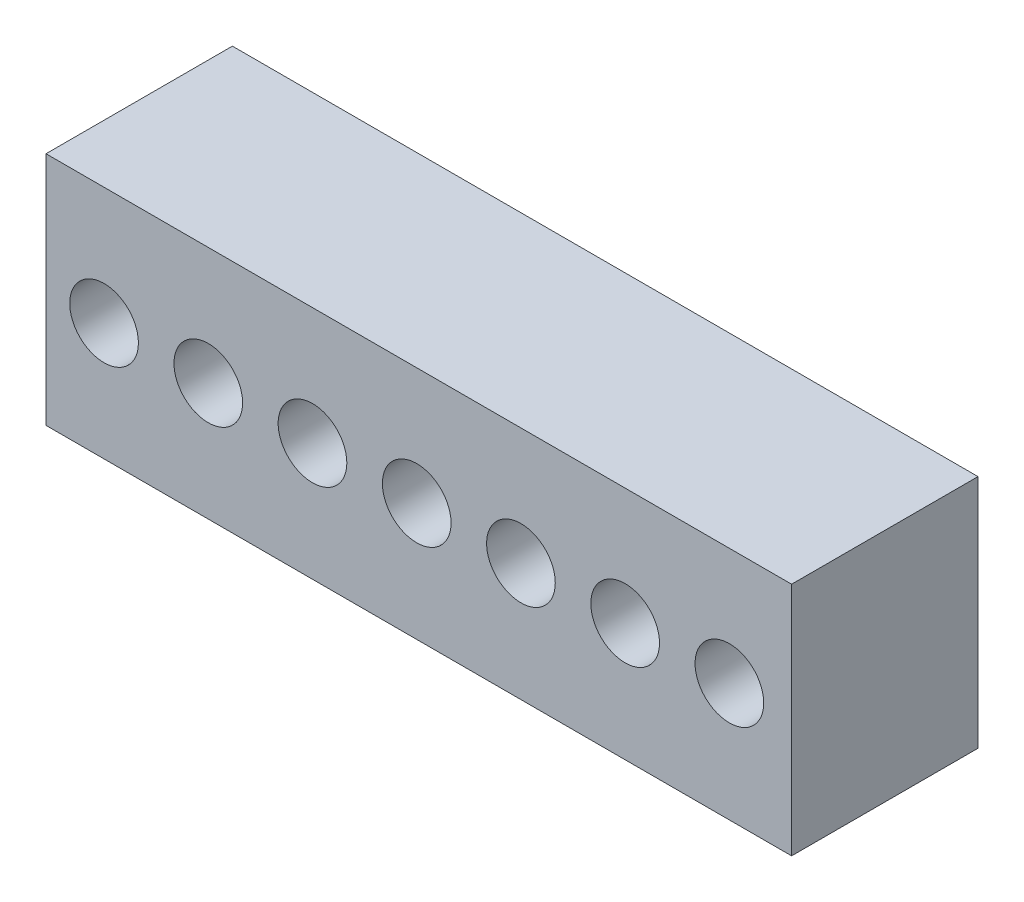
SolidWorks part; units mm, degrees
ref_plane "Front Plane" through (0, 0, 0) normal (0, 0, 1) x (1, 0, 0)
ref_plane "Top Plane" through (0, 0, 0) normal (0, 1, 0) x (1, 0, 0)
ref_plane "Right Plane" through (0, 0, 0) normal (1, 0, 0) x (0, 0, -1)
sketch "Sketch1" plane through (0, 0, 0) normal (0, 0, 1) x (1, 0, 0)
  line L1 (0, 0) -> (16, 0)
  line L2 (0, 0) -> (0, 5.0492)
  line L3 (0, 5.0492) -> (16, 5.0492)
  line L4 (16, 0) -> (16, 5.0492)
  circle A0 centre (1.2459, 2.5246) radius 0.7368
  circle A1 centre (3.4824, 2.5273) radius 0.7368
  circle A2 centre (5.7189, 2.53) radius 0.7368
  circle A3 centre (7.9554, 2.5327) radius 0.7368
  circle A4 centre (10.1919, 2.5355) radius 0.7368
  circle A5 centre (12.4284, 2.5382) radius 0.7368
  circle A6 centre (14.6648, 2.5409) radius 0.7368
  dimension "D1" = 16
  dimension "D2" = 7
extrude "Boss-Extrude1" add sketch "Sketch1" along normal blind 4 contours A6 | A5 | A4 | A3 | A2 | A1 | A0 | L3 L4 L1 L2
